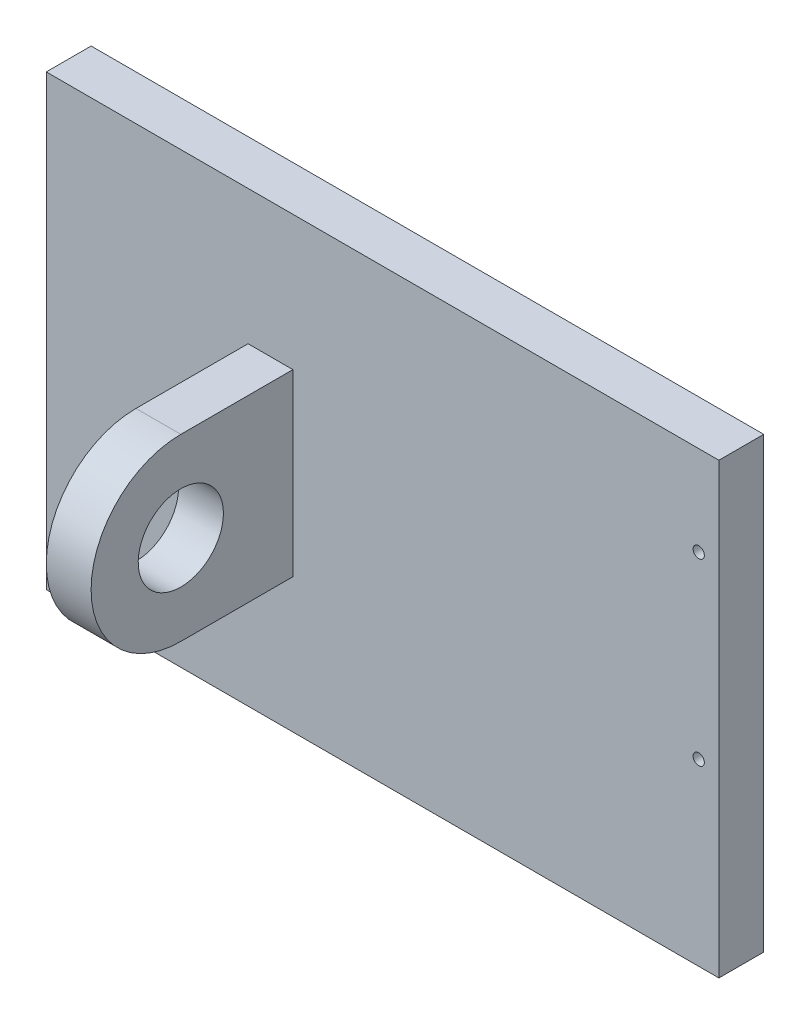
SolidWorks part; units mm, degrees
ref_plane "正面" through (0, 0, 0) normal (0, 0, 1) x (1, 0, 0)
ref_plane "平面" through (0, 0, 0) normal (0, 1, 0) x (1, 0, 0)
ref_plane "右側面" through (0, 0, 0) normal (1, 0, 0) x (0, 0, -1)
sketch "ｽｹｯﾁ2" plane through (0, 0, 0) normal (0, 0, 1) x (1, 0, 0)
  line L1 (-75, 50) -> (75, 50)
  line L2 (-75, 50) -> (-75, -50)
  line L3 (-75, -50) -> (75, -50)
  line L4 (75, 50) -> (75, -50)
  line L5 (-75, 50) -> (75, -50) construction
  line L6 (-75, -50) -> (75, 50) construction
  point P0 (0, 0)
  dimension "D1" = 150
  dimension "D2" = 100
extrude "ﾎﾞｽ - 押し出し1" add sketch "ｽｹｯﾁ2" along normal blind 10
sketch "ｽｹｯﾁ3" plane through (0, 0, 0) normal (0, 0, 1) x (1, 0, 0)
  line L0 (-30, 20) -> (-30, -20)
  line L1 (-30, -20) -> (-20, -20)
  line L2 (-20, -20) -> (-20, 20)
  line L3 (-20, 20) -> (-30, 20)
  dimension "D1" = 10
  dimension "D2" = 20
  dimension "D3" = 20
  dimension "D4" = 20
extrude "ﾎﾞｽ - 押し出し2" add sketch "ｽｹｯﾁ3" along normal blind 35
ref_plane "平面1" through (-30, 0, 0) normal (-1, 0, 0) x (0, 0, 1)
sketch "ｽｹｯﾁ4" plane through (-30, 0, 0) normal (-1, 0, 0) x (0, 0, 1)
  line L0 (35, 20) -> (35, -20) construction
  circle A0 centre (35, 0) radius 20
extrude "ﾎﾞｽ - 押し出し3" add sketch "ｽｹｯﾁ4" against normal blind 10
sketch "ｽｹｯﾁ5" plane through (-30, 0, 0) normal (-1, 0, 0) x (0, 0, 1)
  circle A0 centre (35, 0) radius 9.5
  dimension "D1" = 19
extrude "ｶｯﾄ - 押し出し1" cut sketch "ｽｹｯﾁ5" against normal blind 10
hole_wizard "M3x0.5 ねじ穴2" positions "ｽｹｯﾁ10" profile "ｽｹｯﾁ11" tap size "M3x0.5" standard "JIS" end condition through all
sketch "ｽｹｯﾁ10" plane through (0, 0, 10) normal (0, 0, 1) x (1, 0, 0)
  point P0 (70.5, -10.0009)
  point P3 (70.5, 29.9991)
sketch "ｽｹｯﾁ11" plane through (70.5, -10.0009, 10) normal (1, 0, 0) x (0, -1, 0)
  line L0 (0, 0) -> (0, 10)
  line L1 (0, 10) -> (1.25, 10)
  line L2 (1.25, 10) -> (1.25, 0)
  line L5 (1.25, 0) -> (0, 0)
  line L11 (0, -6.35) -> (0, 107.95) construction
  dimension "次ｻｰﾌｪｽまでのねじ下穴ﾄﾞﾘﾙ直径" = 2.5
  dimension "次ｻｰﾌｪｽまでのねじ下穴ﾄﾞﾘﾙの深さ" = 10
cosmetic thread "穴のねじ山4"
cosmetic thread "穴のねじ山5"
